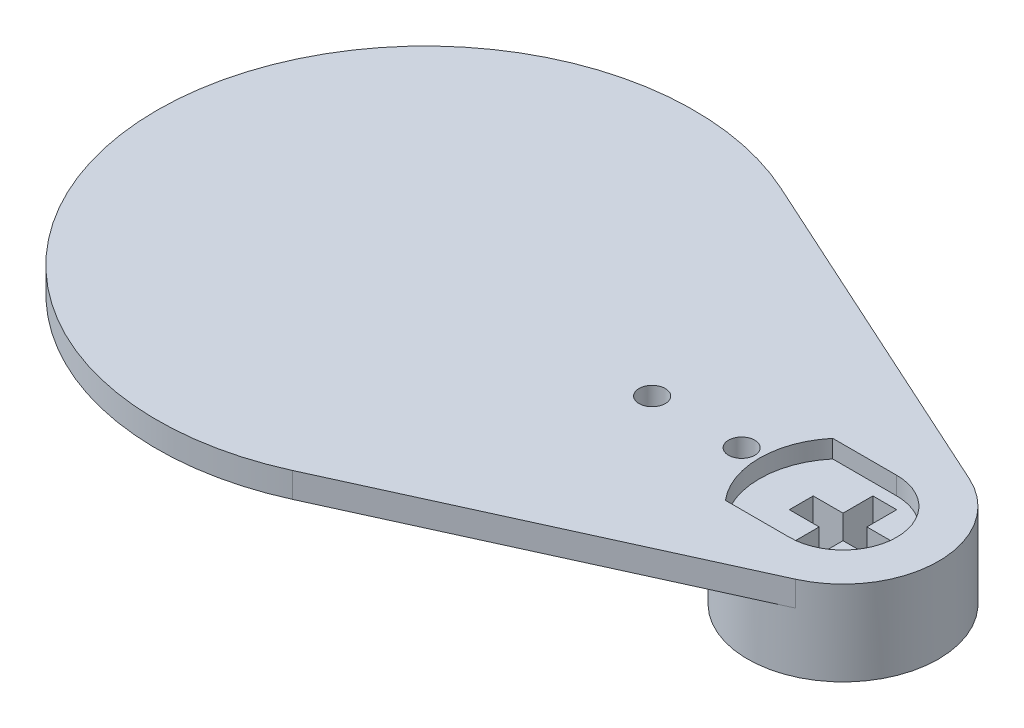
SolidWorks part; units mm, degrees
ref_plane "前视基准面" through (0, 0, 0) normal (0, 0, 1) x (1, 0, 0)
ref_plane "上视基准面" through (0, 0, 0) normal (0, 1, 0) x (1, 0, 0)
ref_plane "右视基准面" through (0, 0, 0) normal (1, 0, 0) x (0, 0, -1)
sketch "草图1" plane through (0, 0, 0) normal (0, 1, 0) x (1, 0, 0)
  line L1 (-25.6786, 20.4783) -> (3.3143, 7.2812)
  line L4 (-25.6786, -20.4783) -> (3.3143, -7.2812)
  line L5 (0, 35) -> (0, 0) construction
  line L6 (0, 0) -> (-35, 0) construction
  arc A8 (3.3143, -7.2812) -> (3.3143, 7.2812) centre (0, 0) ccw
  arc A9 (-25.6786, 20.4783) -> (-25.6786, -20.4783) centre (-35, 0) ccw
  circle A10 centre (0, 0) radius 1
  dimension "D1" = 22.5
  dimension "D2" = 8
  dimension "D3" = 2
  dimension "D4" = 35
extrude "凸台-拉伸1" add sketch "草图1" along normal blind 2.1
sketch "草图3" plane through (0, 2.1, 0) normal (0, 1, 0) x (1, 0, 0)
  line L0 (-5.3619, 4.5) -> (0, 4.5)
  line L1 (-5.3619, -4.5) -> (0, -4.5)
  line L2 (0, 0) -> (-25.5001, 0) construction
  arc A0 (-5.3619, 4.5) -> (-5.3619, -4.5) centre (0, 0) ccw
  arc A1 (0, -4.5) -> (0, 4.5) centre (0, 0) ccw
  dimension "D1" = 14
  dimension "D2" = 9
extrude "切除-拉伸2" cut sketch "草图3" against normal blind 1.5
sketch "草图4" plane through (0, 0, 0) normal (0, -1, 0) x (1, 0, 0)
  circle A0 centre (0, 0) radius 8
  arc A1 (3.3143, -7.2812) -> (3.3143, 7.2812) centre (0, 0) ccw construction
extrude "凸台-拉伸2" add sketch "草图4" along normal blind 5
sketch "草图5" plane through (0, -5, 0) normal (0, -1, 0) x (1, 0, 0)
  line L0 (1, -1) -> (1, -3.5)
  line L1 (-1, 3.5) -> (1, 3.5)
  line L2 (-3.5, 1) -> (-1, 1)
  line L3 (-3.5, 1) -> (-3.5, -1)
  line L4 (-3.5, -1) -> (-1, -1)
  line L5 (3.5, 1) -> (3.5, -1)
  line L6 (-3.5, 1) -> (3.5, -1) construction
  line L7 (-3.5, -1) -> (3.5, 1) construction
  line L8 (-1, 3.5) -> (-1, 1)
  line L9 (-1, -3.5) -> (1, -3.5)
  line L10 (1, 3.5) -> (1, 1)
  line L11 (-1, 3.5) -> (1, -3.5) construction
  line L12 (-1, -3.5) -> (1, 3.5) construction
  line L13 (1, 1) -> (3.5, 1)
  line L14 (-1, -1) -> (-1, -3.5)
  line L15 (1, -1) -> (3.5, -1)
  point P0 (0, 0)
  point P2 (0, 0)
  dimension "D1" = 7
  dimension "D2" = 2
extrude "切除-拉伸3" cut sketch "草图5" against normal through all
sketch "草图2" plane through (0, 2.1, 0) normal (0, 1, 0) x (1, 0, 0)
  circle A0 centre (-8.5, 0) radius 1.1
  circle A1 centre (-16, 0) radius 1.1
  dimension "D1" = 2.2
  dimension "D2" = 8.5
  dimension "D3" = 7.5
extrude "切除-拉伸1" cut sketch "草图2" against normal through all
sketch "草图6" plane through (0, -5, 0) normal (0, -1, 0) x (1, 0, 0)
  circle A0 centre (-8.5, 0) radius 2.5
  dimension "D1" = 5
extrude "切除-拉伸4" cut sketch "草图6" against normal up to surface (5 mm away) up to face at (-16, 0, 1.1)
